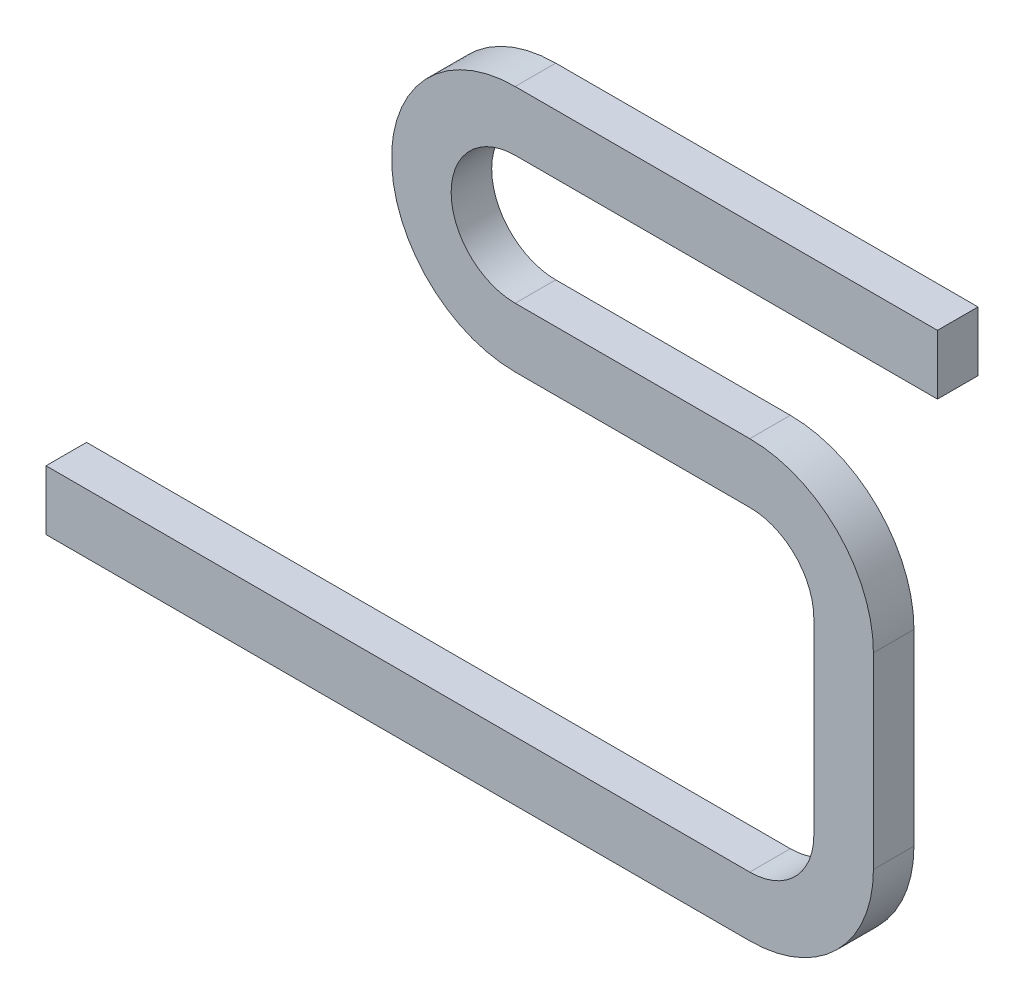
SolidWorks part; units mm, degrees
ref_plane "Front Plane" through (0, 0, 0) normal (0, 0, 1) x (1, 0, 0)
ref_plane "Top Plane" through (0, 0, 0) normal (0, 1, 0) x (1, 0, 0)
ref_plane "Right Plane" through (0, 0, 0) normal (1, 0, 0) x (0, 0, -1)
other "Configuration Table"
sketch "Sketch1" plane through (0, 0, 0) normal (0, 0, 1) x (1, 0, 0)
  line L0 (0, 0) -> (7.5, 0)
  line L1 (8.5, 1) -> (8.5, 3)
  line L2 (7.5, 4) -> (5, 4)
  line L3 (5, 6) -> (9.5, 6)
  arc A0 (7.5, 0) -> (8.5, 1) centre (7.5, 1) ccw
  arc A1 (8.5, 3) -> (7.5, 4) centre (7.5, 3) ccw
  arc A2 (5, 4) -> (5, 6) centre (5, 5) cw
  dimension "D2" = 1
  dimension "D4" = 1
  dimension "D6" = 1
  dimension "D1" = 7.5
  dimension "D3" = 2
  dimension "D5" = 2.5
  dimension "D7" = 4.5
sketch "Sketch2" plane through (0, 0, 0) normal (1, 0, 0) x (0, 0, -1)
  line L1 (-0.216, -0.3175) -> (0.216, -0.3175)
  line L2 (-0.216, -0.3175) -> (-0.216, 0.3175)
  line L3 (-0.216, 0.3175) -> (0.216, 0.3175)
  line L4 (0.216, -0.3175) -> (0.216, 0.3175)
  point P4 (0, -0.3175)
  point P6 (0.216, 0)
  dimension "D1" = 0.432
  dimension "D2" = 0.635
sweep "Sweep1" add profiles "Sketch2" path "Sketch1"
mirror "Mirror1" [suppressed]
